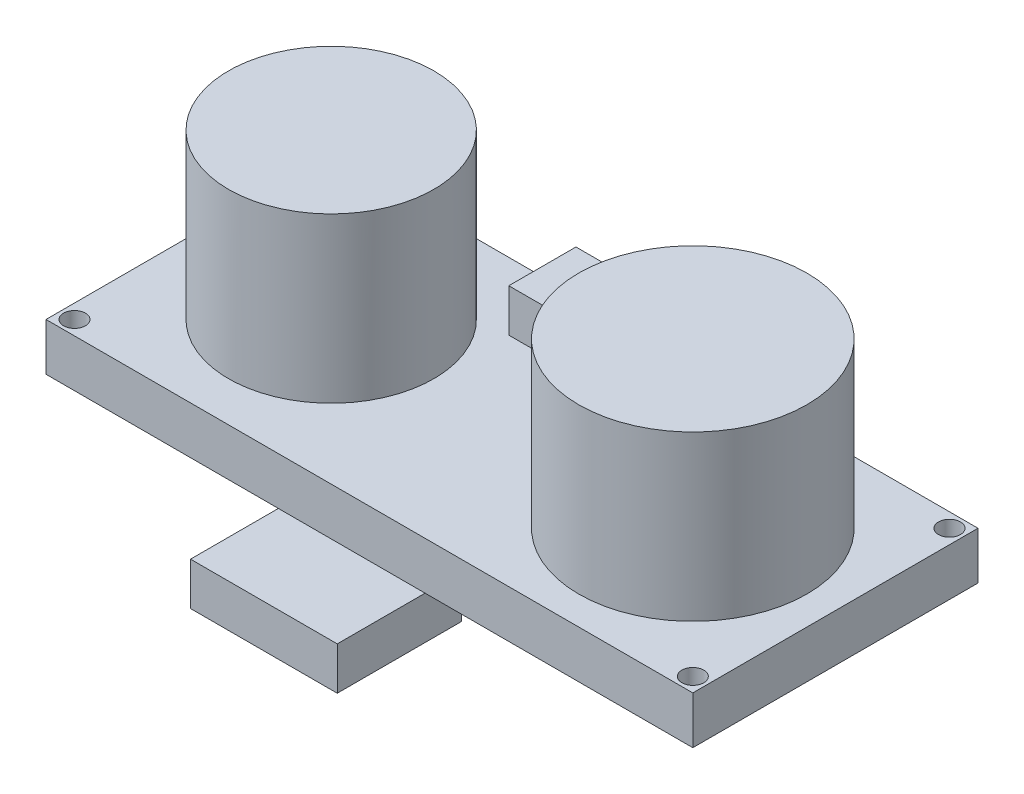
SolidWorks part; units mm, degrees
ref_plane "Front Plane" through (0, 0, 0) normal (0, 0, 1) x (1, 0, 0)
ref_plane "Top Plane" through (0, 0, 0) normal (0, 1, 0) x (1, 0, 0)
ref_plane "Right Plane" through (0, 0, 0) normal (1, 0, 0) x (0, 0, -1)
sketch "Sketch1" plane through (0, 0, 0) normal (0, 1, 0) x (1, 0, 0)
  line L1 (-22.68, -10) -> (22.68, -10)
  line L2 (-22.68, -10) -> (-22.68, 10)
  line L3 (-22.68, 10) -> (22.68, 10)
  line L4 (22.68, -10) -> (22.68, 10)
  line L5 (-22.68, -10) -> (22.68, 10) construction
  line L6 (-22.68, 10) -> (22.68, -10) construction
  point P0 (0, 0)
  dimension "D1" = 45.36
  dimension "D2" = 20
extrude "Boss-Extrude1" add sketch "Sketch1" along normal blind 3.33
sketch "Sketch2" plane through (0, 3.33, 0) normal (0, 1, 0) x (1, 0, 0)
  line L0 (22.68, -10) -> (22.68, 10) construction
  line L1 (-22.68, -10) -> (22.68, -10) construction
  line L2 (-22.68, 10) -> (-22.68, -10) construction
  line L3 (22.68, 10) -> (-22.68, 10) construction
  circle A0 centre (12.68, 0) radius 8
  circle A1 centre (-12.68, 0) radius 7.2018
  dimension "D3" = 16
  dimension "D1" = 10
  dimension "D2" = 10
  dimension "D4" = 10
  dimension "D5" = 10
extrude "Boss-Extrude2" add sketch "Sketch2" along normal blind 11.5
sketch "Sketch3" plane through (0, 3.33, 0) normal (0, 1, 0) x (1, 0, 0)
  line L0 (22.68, -10) -> (22.68, 10) construction
  line L2 (22.68, 10) -> (-22.68, 10) construction
  line L3 (-22.68, -10) -> (22.68, -10) construction
  line L4 (-22.68, 10) -> (-22.68, -10) construction
  circle A0 centre (21.68, 9) radius 0.77
  circle A1 centre (21.68, -9) radius 0.77
  circle A2 centre (-21.68, -9) radius 0.77
  circle A3 centre (-21.68, 9) radius 0.77
  dimension "D3" = 1.54
  dimension "D4" = 1.54
  dimension "D1" = 1
  dimension "D2" = 1
  dimension "D5" = 1
  dimension "D6" = 1
extrude "Cut-Extrude1" cut sketch "Sketch3" against normal blind 11.5
sketch "Sketch4" plane through (0, 3.33, 0) normal (0, 1, 0) x (1, 0, 0)
  line L0 (22.68, 10) -> (-22.68, 10) construction
  line L1 (5.5, 5.275) -> (-5.5, 5.275)
  line L2 (5.5, 5.275) -> (5.5, 9.985)
  line L3 (5.5, 9.985) -> (-5.5, 9.985)
  line L4 (-5.5, 5.275) -> (-5.5, 9.985)
  line L5 (5.5, 5.275) -> (-5.5, 9.985) construction
  line L6 (5.5, 9.985) -> (-5.5, 5.275) construction
  line L7 (-22.68, 10) -> (-22.68, -10) construction
  point P0 (0, 7.63)
  dimension "D1" = 4.71
  dimension "D2" = 11
  dimension "D3" = 2.37
  dimension "D4" = 22.68
extrude "Boss-Extrude3" add sketch "Sketch4" along normal blind 3
sketch "Sketch5" plane through (0, 0, 0) normal (0, -1, 0) x (1, 0, 0)
  line L0 (-22.68, 10) -> (22.68, 10) construction
  line L1 (3.9051, 16.16) -> (-6.3849, 16.16)
  line L2 (3.9051, 16.16) -> (3.9051, 7.46)
  line L3 (3.9051, 7.46) -> (-6.3849, 7.46)
  line L4 (-6.3849, 16.16) -> (-6.3849, 7.46)
  line L5 (3.9051, 16.16) -> (-6.3849, 7.46) construction
  line L6 (3.9051, 7.46) -> (-6.3849, 16.16) construction
  point P0 (-1.2399, 11.81)
  dimension "D1" = 8.7
  dimension "D2" = 10.29
  dimension "D3" = 2.54
extrude "Boss-Extrude4" add sketch "Sketch5" along normal blind 3
